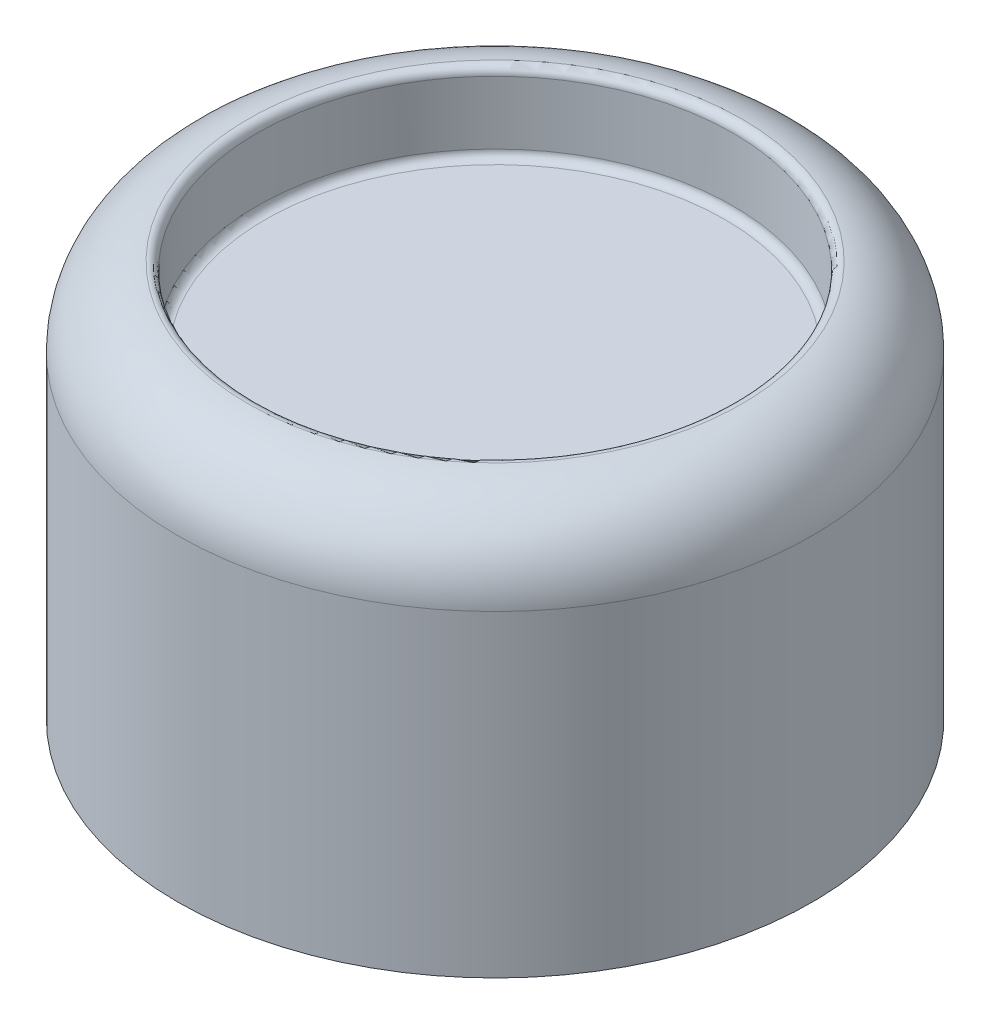
SolidWorks part; units mm, degrees
ref_plane "Front Plane" through (0, 0, 0) normal (0, 0, 1) x (1, 0, 0)
ref_plane "Top Plane" through (0, 0, 0) normal (0, 1, 0) x (1, 0, 0)
ref_plane "Right Plane" through (0, 0, 0) normal (1, 0, 0) x (0, 0, -1)
sketch "Sketch1" plane through (0, 0, 0) normal (0, 1, 0) x (1, 0, 0)
  circle A0 centre (0, 0) radius 4
extrude "Boss-Extrude1" add sketch "Sketch1" along normal blind 5
fillet "Fillet1" radius 1 1 edges at (0, 5, 4)
sketch "Sketch2" plane through (0, 5, 0) normal (0, 1, 0) x (1, 0, 0)
  circle A0 centre (0, 0) radius 3
extrude "Cut-Extrude1" cut sketch "Sketch2" against normal blind 1
fillet "Fillet2" radius 0.1 2 edges at (0, 4, 3) (0, 5, 3)
sketch "Sketch3" plane through (0, 0, 0) normal (0, -1, 0) x (1, 0, 0)
  circle A0 centre (0, 0) radius 3
  circle A1 centre (0, 0) radius 1.2
extrude "Cut-Extrude3" cut sketch "Sketch3" against normal blind 3.5
sketch "Sketch4" plane through (0, 0, 0) normal (0, -1, 0) x (1, 0, 0)
  circle A0 centre (0, 0) radius 0.5
extrude "Cut-Extrude4" cut sketch "Sketch4" against normal blind 3.5
fillet "Fillet3" radius 0.5 1 edges at (0, 0, -1.2)
